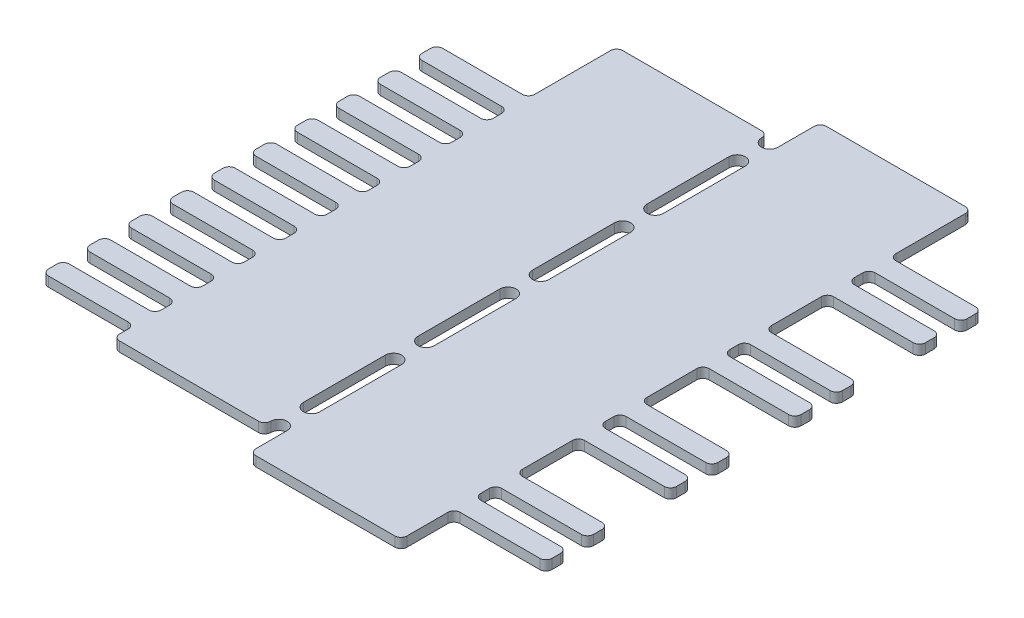
SolidWorks part; units mm, degrees
ref_plane "Front Plane" through (0, 0, 0) normal (0, 0, 1) x (1, 0, 0)
ref_plane "Top Plane" through (0, 0, 0) normal (0, 1, 0) x (1, 0, 0)
ref_plane "Right Plane" through (0, 0, 0) normal (1, 0, 0) x (0, 0, -1)
sketch "Sketch1" plane through (0, 0, 0) normal (0, 1, 0) x (1, 0, 0)
  line L0 (-0.75, 10) -> (-10.5, 10)
  line L2 (0, 9.25) -> (0, 0.75)
  line L5 (-11.25, 11.27) -> (0, 11.27) construction
  line L7 (-11.25, 10.75) -> (-11.25, 11.79)
  line L8 (-10.5, 12.54) -> (-0.75, 12.54)
  line L12 (0, 14.33) -> (0, 13.29)
  line L17 (-0.75, 15.08) -> (-10.5, 15.08)
  line L22 (-11.25, 15.83) -> (-11.25, 16.87)
  line L27 (-10.5, 17.62) -> (-0.75, 17.62)
  line L56 (17.75, 0) -> (0.75, 0)
  line L84 (0, 19.41) -> (0, 10.91) [skipped]
  line L85 (-0.75, 20.16) -> (-10.5, 20.16) [skipped]
  line L86 (-11.25, 20.91) -> (-11.25, 21.95) [skipped]
  line L87 (-10.5, 22.7) -> (-0.75, 22.7) [skipped]
  line L88 (0, 24.49) -> (0, 15.99) [skipped]
  line L89 (-0.75, 25.24) -> (-10.5, 25.24) [skipped]
  line L90 (-11.25, 25.99) -> (-11.25, 27.03) [skipped]
  line L91 (-10.5, 27.78) -> (-0.75, 27.78) [skipped]
  line L92 (0, 29.57) -> (0, 21.07) [skipped]
  line L93 (-0.75, 30.32) -> (-10.5, 30.32) [skipped]
  line L94 (-11.25, 31.07) -> (-11.25, 32.11) [skipped]
  line L95 (-10.5, 32.86) -> (-0.75, 32.86) [skipped]
  line L96 (0, 34.65) -> (0, 26.15) [skipped]
  line L97 (-0.75, 35.4) -> (-10.5, 35.4) [skipped]
  line L98 (-11.25, 36.15) -> (-11.25, 37.19) [skipped]
  line L99 (-10.5, 37.94) -> (-0.75, 37.94) [skipped]
  line L100 (0, 39.73) -> (0, 31.23) [skipped]
  line L101 (-0.75, 40.48) -> (-10.5, 40.48) [skipped]
  line L102 (-11.25, 41.23) -> (-11.25, 42.27) [skipped]
  line L103 (-10.5, 43.02) -> (-0.75, 43.02) [skipped]
  line L104 (0, 44.81) -> (0, 36.31) [skipped]
  line L105 (-0.75, 45.56) -> (-10.5, 45.56) [skipped]
  line L106 (-11.25, 46.31) -> (-11.25, 47.35) [skipped]
  line L107 (-10.5, 48.1) -> (-0.75, 48.1) [skipped]
  line L108 (0, 49.89) -> (0, 41.39) [skipped]
  line L109 (-0.75, 50.64) -> (-10.5, 50.64) [skipped]
  line L110 (-11.25, 51.39) -> (-11.25, 52.43) [skipped]
  line L111 (-10.5, 53.18) -> (-0.75, 53.18) [skipped]
  line L112 (0, 54.97) -> (0, 46.47) [skipped]
  line L113 (-0.75, 55.72) -> (-10.5, 55.72) [skipped]
  line L114 (-11.25, 56.47) -> (-11.25, 57.51) [skipped]
  line L115 (-10.5, 58.26) -> (-0.75, 58.26) [skipped]
  line L116 (-0.75, 25.24) -> (-10.5, 25.24)
  line L117 (-11.25, 25.99) -> (-11.25, 27.03)
  line L118 (-10.5, 27.78) -> (-0.75, 27.78)
  line L119 (0, 29.57) -> (0, 28.53)
  line L120 (-0.75, 30.32) -> (-10.5, 30.32)
  line L121 (-11.25, 31.07) -> (-11.25, 32.11)
  line L122 (-10.5, 32.86) -> (-0.75, 32.86)
  line L123 (-0.75, 40.48) -> (-10.5, 40.48)
  line L124 (-11.25, 41.23) -> (-11.25, 42.27)
  line L125 (-10.5, 43.02) -> (-0.75, 43.02)
  line L126 (0, 44.81) -> (0, 43.77)
  line L127 (-0.75, 45.56) -> (-10.5, 45.56)
  line L128 (-11.25, 46.31) -> (-11.25, 47.35)
  line L129 (-10.5, 48.1) -> (-0.75, 48.1)
  line L130 (-0.75, 55.72) -> (-10.5, 55.72)
  line L131 (-11.25, 56.47) -> (-11.25, 57.51)
  line L132 (-10.5, 58.26) -> (-0.75, 58.26)
  line L133 (0, 60.05) -> (0, 59.01)
  line L134 (-0.75, 60.8) -> (-10.5, 60.8)
  line L135 (-11.25, 61.55) -> (-11.25, 62.59)
  line L136 (-10.5, 63.34) -> (-0.75, 63.34)
  line L137 (0, 24.49) -> (0, 18.37)
  line L138 (0, 33.61) -> (0, 39.73)
  line L139 (0, 48.85) -> (0, 54.97)
  line L140 (0, 64.09) -> (0, 69.09)
  line L141 (0.75, 69.84) -> (17.75, 69.84)
  line L145 (39.75, 15.2205) -> (49.5, 15.2205)
  line L157 (39, 14.4705) -> (39, 5.183)
  line L158 (38.25, 4.433) -> (21.25, 4.433)
  line L160 (21.25, 66.0205) -> (38.25, 66.0205)
  line L188 (19.5, 5.183) -> (19.5, 56.2098) construction
  line L190 (18.5, 0.75) -> (18.5, 5.183)
  line L191 (20.5, 5.183) -> (19.5, 5.183) construction
  line L192 (20.5, 65.2705) -> (19.5, 65.2705) construction
  line L193 (20, 56.7098) -> (20, 60.84) construction
  line L194 (19, 60.84) -> (19, 56.7098) construction
  line L195 (18.5, 65.2705) -> (18.5, 69.09)
  line L196 (19.5, 56.2098) -> (19.5, 57.2098) construction
  line L197 (19.5, 57.2098) -> (19.5, 60.34) construction
  line L198 (19.5, 60.34) -> (19.5, 61.34) construction
  line L199 (19.5, 61.34) -> (19.5, 65.2705) construction
  line L200 (50.25, 15.9705) -> (50.25, 17.0105)
  line L201 (49.5, 17.7605) -> (39.75, 17.7605)
  line L202 (39, 18.5105) -> (39, 19.5505)
  line L204 (50.25, 21.0505) -> (50.25, 22.0905)
  line L205 (49.5, 22.8405) -> (39.75, 22.8405)
  line L206 (39, 23.5905) -> (39, 24.6305)
  line L207 (39.75, 20.3005) -> (49.5, 20.3005)
  line L208 (50.25, 26.1305) -> (50.25, 27.1705)
  line L209 (49.5, 27.9205) -> (39.75, 27.9205)
  line L210 (39, 28.6705) -> (39, 29.7105)
  line L212 (19.5, 65.2705) -> (18.5, 65.2705) construction
  line L213 (19.5, 65.2705) -> (19.5, 59.9038) construction
  line L214 (39.75, 25.3805) -> (49.5, 25.3805)
  line L215 (50.25, 31.2105) -> (50.25, 32.2505)
  line L216 (49.5, 33.0005) -> (39.75, 33.0005)
  line L217 (39, 33.7505) -> (39, 34.7905)
  line L218 (19.5, 5.183) -> (18.5, 5.183) construction
  line L219 (39.75, 30.4605) -> (49.5, 30.4605)
  line L220 (50.25, 36.2905) -> (50.25, 37.3305)
  line L221 (49.5, 38.0805) -> (39.75, 38.0805)
  line L222 (39, 38.8305) -> (39, 39.8705)
  line L223 (39.75, 35.5405) -> (49.5, 35.5405)
  line L224 (50.25, 41.3705) -> (50.25, 42.4105)
  line L225 (49.5, 43.1605) -> (39.75, 43.1605)
  line L226 (39, 43.9105) -> (39, 44.9505)
  line L227 (39.75, 40.6205) -> (49.5, 40.6205)
  line L228 (50.25, 46.4505) -> (50.25, 47.4905)
  line L229 (49.5, 48.2405) -> (39.75, 48.2405)
  line L230 (39, 48.9905) -> (39, 50.0305)
  line L231 (39.75, 45.7005) -> (49.5, 45.7005)
  line L232 (50.25, 51.5305) -> (50.25, 52.5705)
  line L233 (49.5, 53.3205) -> (39.75, 53.3205)
  line L234 (39, 54.0705) -> (39, 55.1105)
  line L235 (39.75, 50.7805) -> (49.5, 50.7805)
  line L236 (50.25, 56.6105) -> (50.25, 57.6505)
  line L237 (49.5, 58.4005) -> (39.75, 58.4005)
  line L238 (39, 59.1505) -> (39, 60.1905)
  line L239 (39.75, 55.8605) -> (49.5, 55.8605)
  line L240 (50.25, 61.6905) -> (50.25, 62.7305)
  line L241 (49.5, 63.4805) -> (39.75, 63.4805)
  line L242 (39, 64.2305) -> (39, 65.2705)
  line L243 (39.75, 60.9405) -> (49.5, 60.9405)
  arc A0 (-0.75, 12.54) -> (0, 13.29) centre (-0.75, 13.29) ccw
  arc A1 (-11.25, 11.79) -> (-10.5, 12.54) centre (-10.5, 11.79) cw
  arc A2 (-10.5, 10) -> (-11.25, 10.75) centre (-10.5, 10.75) cw
  arc A3 (0, 0.75) -> (0.75, 0) centre (0.75, 0.75) ccw
  arc A4 (-0.75, 10) -> (0, 9.25) centre (-0.75, 9.25) cw
  arc A5 (18.5, 0.75) -> (17.75, 0) centre (17.75, 0.75) cw
  arc A6 (-0.75, 15.08) -> (0, 14.33) centre (-0.75, 14.33) cw
  arc A7 (-10.5, 15.08) -> (-11.25, 15.83) centre (-10.5, 15.83) cw
  arc A8 (-11.25, 16.87) -> (-10.5, 17.62) centre (-10.5, 16.87) cw
  arc A9 (-0.75, 17.62) -> (0, 18.37) centre (-0.75, 18.37) ccw
  arc A44 (-0.75, 20.16) -> (0, 19.41) centre (-0.75, 19.41) cw [skipped]
  arc A45 (-10.5, 20.16) -> (-11.25, 20.91) centre (-10.5, 20.91) cw [skipped]
  arc A46 (-11.25, 21.95) -> (-10.5, 22.7) centre (-10.5, 21.95) cw [skipped]
  arc A47 (-0.75, 22.7) -> (0, 23.45) centre (-0.75, 23.45) ccw [skipped]
  arc A48 (-0.75, 25.24) -> (0, 24.49) centre (-0.75, 24.49) cw [skipped]
  arc A49 (-10.5, 25.24) -> (-11.25, 25.99) centre (-10.5, 25.99) cw [skipped]
  arc A50 (-11.25, 27.03) -> (-10.5, 27.78) centre (-10.5, 27.03) cw [skipped]
  arc A51 (-0.75, 27.78) -> (0, 28.53) centre (-0.75, 28.53) ccw [skipped]
  arc A52 (-0.75, 30.32) -> (0, 29.57) centre (-0.75, 29.57) cw [skipped]
  arc A53 (-10.5, 30.32) -> (-11.25, 31.07) centre (-10.5, 31.07) cw [skipped]
  arc A54 (-11.25, 32.11) -> (-10.5, 32.86) centre (-10.5, 32.11) cw [skipped]
  arc A55 (-0.75, 32.86) -> (0, 33.61) centre (-0.75, 33.61) ccw [skipped]
  arc A56 (-0.75, 35.4) -> (0, 34.65) centre (-0.75, 34.65) cw [skipped]
  arc A57 (-10.5, 35.4) -> (-11.25, 36.15) centre (-10.5, 36.15) cw [skipped]
  arc A58 (-11.25, 37.19) -> (-10.5, 37.94) centre (-10.5, 37.19) cw [skipped]
  arc A59 (-0.75, 37.94) -> (0, 38.69) centre (-0.75, 38.69) ccw [skipped]
  arc A60 (-0.75, 40.48) -> (0, 39.73) centre (-0.75, 39.73) cw [skipped]
  arc A61 (-10.5, 40.48) -> (-11.25, 41.23) centre (-10.5, 41.23) cw [skipped]
  arc A62 (-11.25, 42.27) -> (-10.5, 43.02) centre (-10.5, 42.27) cw [skipped]
  arc A63 (-0.75, 43.02) -> (0, 43.77) centre (-0.75, 43.77) ccw [skipped]
  arc A64 (-0.75, 45.56) -> (0, 44.81) centre (-0.75, 44.81) cw [skipped]
  arc A65 (-10.5, 45.56) -> (-11.25, 46.31) centre (-10.5, 46.31) cw [skipped]
  arc A66 (-11.25, 47.35) -> (-10.5, 48.1) centre (-10.5, 47.35) cw [skipped]
  arc A67 (-0.75, 48.1) -> (0, 48.85) centre (-0.75, 48.85) ccw [skipped]
  arc A68 (-0.75, 50.64) -> (0, 49.89) centre (-0.75, 49.89) cw [skipped]
  arc A69 (-10.5, 50.64) -> (-11.25, 51.39) centre (-10.5, 51.39) cw [skipped]
  arc A70 (-11.25, 52.43) -> (-10.5, 53.18) centre (-10.5, 52.43) cw [skipped]
  arc A71 (-0.75, 53.18) -> (0, 53.93) centre (-0.75, 53.93) ccw [skipped]
  arc A72 (-0.75, 55.72) -> (0, 54.97) centre (-0.75, 54.97) cw [skipped]
  arc A73 (-10.5, 55.72) -> (-11.25, 56.47) centre (-10.5, 56.47) cw [skipped]
  arc A74 (-11.25, 57.51) -> (-10.5, 58.26) centre (-10.5, 57.51) cw [skipped]
  arc A75 (-0.75, 58.26) -> (0, 59.01) centre (-0.75, 59.01) ccw [skipped]
  arc A76 (-0.75, 27.78) -> (0, 28.53) centre (-0.75, 28.53) ccw
  arc A77 (-11.25, 27.03) -> (-10.5, 27.78) centre (-10.5, 27.03) cw
  arc A78 (-10.5, 25.24) -> (-11.25, 25.99) centre (-10.5, 25.99) cw
  arc A79 (-0.75, 25.24) -> (0, 24.49) centre (-0.75, 24.49) cw
  arc A80 (-0.75, 30.32) -> (0, 29.57) centre (-0.75, 29.57) cw
  arc A81 (-10.5, 30.32) -> (-11.25, 31.07) centre (-10.5, 31.07) cw
  arc A82 (-11.25, 32.11) -> (-10.5, 32.86) centre (-10.5, 32.11) cw
  arc A83 (-0.75, 32.86) -> (0, 33.61) centre (-0.75, 33.61) ccw
  arc A84 (-0.75, 43.02) -> (0, 43.77) centre (-0.75, 43.77) ccw
  arc A85 (-11.25, 42.27) -> (-10.5, 43.02) centre (-10.5, 42.27) cw
  arc A86 (-10.5, 40.48) -> (-11.25, 41.23) centre (-10.5, 41.23) cw
  arc A87 (-0.75, 40.48) -> (0, 39.73) centre (-0.75, 39.73) cw
  arc A88 (-0.75, 45.56) -> (0, 44.81) centre (-0.75, 44.81) cw
  arc A89 (-10.5, 45.56) -> (-11.25, 46.31) centre (-10.5, 46.31) cw
  arc A90 (-11.25, 47.35) -> (-10.5, 48.1) centre (-10.5, 47.35) cw
  arc A91 (-0.75, 48.1) -> (0, 48.85) centre (-0.75, 48.85) ccw
  arc A92 (-0.75, 58.26) -> (0, 59.01) centre (-0.75, 59.01) ccw
  arc A93 (-11.25, 57.51) -> (-10.5, 58.26) centre (-10.5, 57.51) cw
  arc A94 (-10.5, 55.72) -> (-11.25, 56.47) centre (-10.5, 56.47) cw
  arc A95 (-0.75, 55.72) -> (0, 54.97) centre (-0.75, 54.97) cw
  arc A96 (-0.75, 60.8) -> (0, 60.05) centre (-0.75, 60.05) cw
  arc A97 (-10.5, 60.8) -> (-11.25, 61.55) centre (-10.5, 61.55) cw
  arc A98 (-11.25, 62.59) -> (-10.5, 63.34) centre (-10.5, 62.59) cw
  arc A99 (-0.75, 63.34) -> (0, 64.09) centre (-0.75, 64.09) ccw
  arc A100 (0, 69.09) -> (0.75, 69.84) centre (0.75, 69.09) cw
  arc A101 (17.75, 69.84) -> (18.5, 69.09) centre (17.75, 69.09) cw
  arc A107 (20.5, 65.2705) -> (21.25, 66.0205) centre (21.25, 65.2705) cw
  arc A144 (39, 5.183) -> (38.25, 4.433) centre (38.25, 5.183) cw
  arc A145 (21.25, 4.433) -> (20.5, 5.183) centre (21.25, 5.183) cw
  arc A147 (20.5, 5.183) -> (18.5, 5.183) centre (19.5, 5.183) ccw
  arc A148 (18.5, 5.183) -> (20.5, 5.183) centre (19.5, 5.183) ccw construction
  arc A149 (20, 60.84) -> (19, 60.84) centre (19.5, 60.84) ccw construction
  arc A150 (19, 56.7098) -> (20, 56.7098) centre (19.5, 56.7098) ccw construction
  arc A151 (19.5, 57.2098) -> (19, 56.7098) centre (19.5, 56.7098) ccw construction
  arc A152 (20, 56.7098) -> (19.5, 57.2098) centre (19.5, 56.7098) ccw construction
  arc A153 (19.5, 60.34) -> (20, 60.84) centre (19.5, 60.84) ccw construction
  arc A154 (19, 60.84) -> (19.5, 60.34) centre (19.5, 60.84) ccw construction
  arc A155 (18.5, 65.2705) -> (20.5, 65.2705) centre (19.5, 65.2705) ccw
  arc A156 (20.5, 65.2705) -> (18.5, 65.2705) centre (19.5, 65.2705) ccw construction
  arc A157 (39.75, 17.7605) -> (39, 18.5105) centre (39.75, 18.5105) cw
  arc A158 (50.25, 17.0105) -> (49.5, 17.7605) centre (49.5, 17.0105) ccw
  arc A159 (49.5, 15.2205) -> (50.25, 15.9705) centre (49.5, 15.9705) ccw
  arc A160 (39, 14.4705) -> (39.75, 15.2205) centre (39.75, 14.4705) cw
  arc A161 (39.75, 22.8405) -> (39, 23.5905) centre (39.75, 23.5905) cw
  arc A162 (50.25, 22.0905) -> (49.5, 22.8405) centre (49.5, 22.0905) ccw
  arc A163 (49.5, 20.3005) -> (50.25, 21.0505) centre (49.5, 21.0505) ccw
  arc A164 (39, 19.5505) -> (39.75, 20.3005) centre (39.75, 19.5505) cw
  arc A165 (39.75, 27.9205) -> (39, 28.6705) centre (39.75, 28.6705) cw
  arc A166 (50.25, 27.1705) -> (49.5, 27.9205) centre (49.5, 27.1705) ccw
  arc A167 (49.5, 25.3805) -> (50.25, 26.1305) centre (49.5, 26.1305) ccw
  arc A168 (39, 24.6305) -> (39.75, 25.3805) centre (39.75, 24.6305) cw
  arc A169 (39.75, 33.0005) -> (39, 33.7505) centre (39.75, 33.7505) cw
  arc A170 (50.25, 32.2505) -> (49.5, 33.0005) centre (49.5, 32.2505) ccw
  arc A171 (49.5, 30.4605) -> (50.25, 31.2105) centre (49.5, 31.2105) ccw
  arc A172 (39, 29.7105) -> (39.75, 30.4605) centre (39.75, 29.7105) cw
  arc A173 (39.75, 38.0805) -> (39, 38.8305) centre (39.75, 38.8305) cw
  arc A174 (50.25, 37.3305) -> (49.5, 38.0805) centre (49.5, 37.3305) ccw
  arc A175 (49.5, 35.5405) -> (50.25, 36.2905) centre (49.5, 36.2905) ccw
  arc A176 (39, 34.7905) -> (39.75, 35.5405) centre (39.75, 34.7905) cw
  arc A177 (39.75, 43.1605) -> (39, 43.9105) centre (39.75, 43.9105) cw
  arc A178 (50.25, 42.4105) -> (49.5, 43.1605) centre (49.5, 42.4105) ccw
  arc A179 (49.5, 40.6205) -> (50.25, 41.3705) centre (49.5, 41.3705) ccw
  arc A180 (39, 39.8705) -> (39.75, 40.6205) centre (39.75, 39.8705) cw
  arc A181 (39.75, 48.2405) -> (39, 48.9905) centre (39.75, 48.9905) cw
  arc A182 (50.25, 47.4905) -> (49.5, 48.2405) centre (49.5, 47.4905) ccw
  arc A183 (49.5, 45.7005) -> (50.25, 46.4505) centre (49.5, 46.4505) ccw
  arc A184 (39, 44.9505) -> (39.75, 45.7005) centre (39.75, 44.9505) cw
  arc A185 (39.75, 53.3205) -> (39, 54.0705) centre (39.75, 54.0705) cw
  arc A186 (50.25, 52.5705) -> (49.5, 53.3205) centre (49.5, 52.5705) ccw
  arc A187 (49.5, 50.7805) -> (50.25, 51.5305) centre (49.5, 51.5305) ccw
  arc A188 (39, 50.0305) -> (39.75, 50.7805) centre (39.75, 50.0305) cw
  arc A189 (39.75, 58.4005) -> (39, 59.1505) centre (39.75, 59.1505) cw
  arc A190 (50.25, 57.6505) -> (49.5, 58.4005) centre (49.5, 57.6505) ccw
  arc A191 (49.5, 55.8605) -> (50.25, 56.6105) centre (49.5, 56.6105) ccw
  arc A192 (39, 55.1105) -> (39.75, 55.8605) centre (39.75, 55.1105) cw
  arc A193 (39.75, 63.4805) -> (39, 64.2305) centre (39.75, 64.2305) cw
  arc A194 (50.25, 62.7305) -> (49.5, 63.4805) centre (49.5, 62.7305) ccw
  arc A195 (49.5, 60.9405) -> (50.25, 61.6905) centre (49.5, 61.6905) ccw
  arc A196 (39, 60.1905) -> (39.75, 60.9405) centre (39.75, 60.1905) cw
  arc A197 (39, 65.2705) -> (38.25, 66.0205) centre (38.25, 65.2705) ccw
  point P0 (0, 0)
  point P48 (-11.25, 12.54)
  point P69 (-11.25, 10)
  point P78 (0, 0)
  point P81 (0, 10)
  point P132 (29.75, 4.433)
  point P390 (44.625, 15.2205)
  dimension "D6" = 0.75
  dimension "D7" = 0.75
  dimension "D8" = 4
  dimension "D9" = 10.16
  dimension "D11" = 0.75
  dimension "D13" = 4.433
  dimension "D14" = 0.75
  dimension "D15" = 9
  dimension "D16" = 0.75
  dimension "D12" = 6.5
  dimension "D21" = 0.75
  dimension "D22" = 18.5
  dimension "D5" = 2
  dimension "D24" = 4.1302
  dimension "D25" = 18.5
  dimension "D17" = 0.75
  dimension "D1" = 2.54
  dimension "D2" = 10.5
  dimension "D3" = 10
  dimension "D4" = 10
  dimension "D10" = 5.08
  dimension "D18" = 10
  dimension "D19" = 10.5
  dimension "D20" = 2.54
  dimension "D23" = 5.08
  dimension "D26" = 10.7875
  dimension "D27" = 69.84
  dimension "D28" = 3.8195
  dimension "D29" = 3.8195
extrude "Boss-Extrude1" add sketch "Sketch1" along normal blind 1.2
sketch "Sketch2" plane through (0, 0, 0) normal (0, -1, 0) x (1, 0, 0)
  line L0 (19.5, -5.183) -> (19.5, -65.2705) construction
  line L1 (19.5, -61.2705) -> (19.5, -51.2505) construction
  line L2 (18.5, -61.2705) -> (18.5, -51.2505)
  line L3 (20.5, -61.2705) -> (20.5, -51.2505)
  line L4 (19.5, -35.2268) -> (0, -35.2268) construction
  line L5 (0, -39.73) -> (0, -33.61) construction
  line L6 (19.5, -47.2505) -> (19.5, -37.2305) construction
  line L7 (18.5, -47.2505) -> (18.5, -37.2305)
  line L8 (20.5, -47.2505) -> (20.5, -37.2305)
  line L9 (19.5, -23.203) -> (19.5, -33.223) construction
  line L10 (18.5, -23.203) -> (18.5, -33.223)
  line L11 (20.5, -23.203) -> (20.5, -33.223)
  line L12 (19.5, -9.183) -> (19.5, -19.203) construction
  line L13 (18.5, -9.183) -> (18.5, -19.203)
  line L14 (20.5, -9.183) -> (20.5, -19.203)
  arc A0 (18.5, -61.2705) -> (20.5, -61.2705) centre (19.5, -61.2705) ccw
  arc A1 (20.5, -51.2505) -> (18.5, -51.2505) centre (19.5, -51.2505) ccw
  circle A2 centre (19.5, -65.2705) radius 1 construction
  arc A3 (20.5, -65.2705) -> (18.5, -65.2705) centre (19.5, -65.2705) ccw construction
  arc A4 (18.5, -47.2505) -> (20.5, -47.2505) centre (19.5, -47.2505) ccw
  arc A5 (20.5, -37.2305) -> (18.5, -37.2305) centre (19.5, -37.2305) ccw
  arc A6 (18.5, -23.203) -> (20.5, -23.203) centre (19.5, -23.203) cw
  arc A7 (20.5, -33.223) -> (18.5, -33.223) centre (19.5, -33.223) cw
  arc A8 (18.5, -9.183) -> (20.5, -9.183) centre (19.5, -9.183) cw
  arc A9 (20.5, -19.203) -> (18.5, -19.203) centre (19.5, -19.203) cw
  point P6 (19.5, -56.2605)
  point P23 (19.5, -42.2405)
  point P28 (19.5, -28.213)
  point P35 (19.5, -14.193)
  dimension "D4" = 4
  dimension "D1" = 10.02
  dimension "D2" = 4
  dimension "D3" = 2
extrude "Cut-Extrude1" cut sketch "Sketch2" against normal through all
move or copy body "Body-Move/Copy1" bodies to move or copy 102 copy no rotation origin (17.625, 0, -34.92) rotation axis (0, 1, 0) rotation angle 180
equation "\"T\"= 1"
